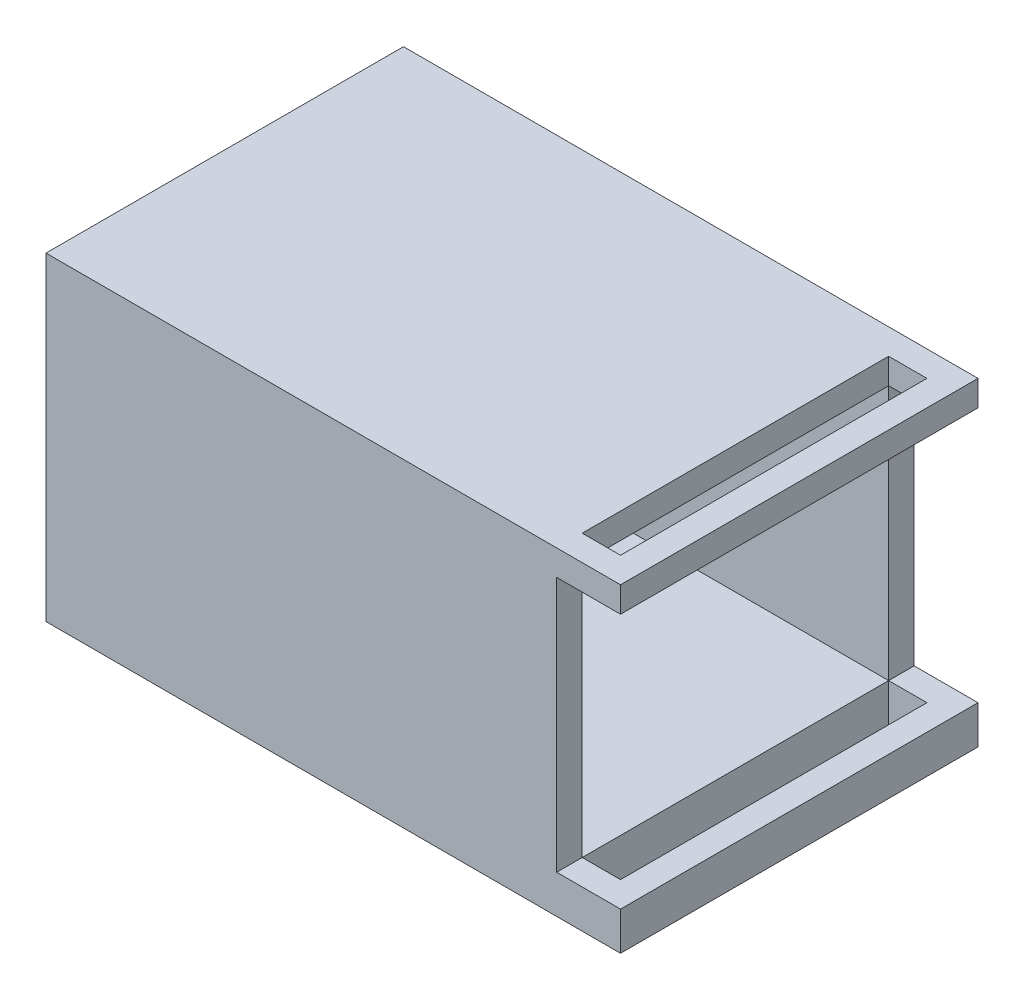
SolidWorks part; units mm, degrees
ref_plane "Front Plane" through (0, 0, 0) normal (0, 0, 1) x (1, 0, 0)
ref_plane "Top Plane" through (0, 0, 0) normal (0, 1, 0) x (1, 0, 0)
ref_plane "Right Plane" through (0, 0, 0) normal (1, 0, 0) x (0, 0, -1)
sketch "Sketch1" plane through (0, 0, 0) normal (0, 1, 0) x (1, 0, 0)
  line L1 (0, 0) -> (45, 0)
  line L2 (0, 0) -> (0, 28)
  line L3 (0, 28) -> (45, 28)
  line L4 (45, 0) -> (45, 28)
  dimension "D1" = 28
  dimension "D2" = 45
extrude "Boss-Extrude1" add sketch "Sketch1" along normal blind 3 contours L2 L1 L4 L3
sketch "Sketch2" plane through (0, 3, 0) normal (0, 1, 0) x (1, 0, 0)
  line L0 (40, 26) -> (40, 28)
  line L1 (0, 28) -> (40, 28)
  line L2 (0, 28) -> (0, 0)
  line L3 (0, 0) -> (40, 0)
  line L5 (2, 26) -> (40, 26)
  line L6 (2, 26) -> (2, 2)
  line L7 (2, 2) -> (40, 2)
  line L9 (40, 2) -> (40, 0)
  line L10 (45, 0) -> (45, 28) construction
  line L11 (0, 0) -> (45, 0) construction
  dimension "D1" = 2
  dimension "D2" = 2
  dimension "D3" = 2
  dimension "D4" = 5
  dimension "D5" = 5
extrude "Boss-Extrude2" add sketch "Sketch2" along normal blind 22 contours L5 L0 L1 L2 L3 L9 L7 L6
sketch "Sketch4" plane through (0, 25, 0) normal (0, 1, 0) x (1, 0, 0)
  line L0 (0, 28) -> (40, 28) construction
  line L1 (0, 28) -> (45, 28)
  line L2 (0, 28) -> (0, 0)
  line L3 (0, 0) -> (45, 0)
  line L4 (45, 28) -> (45, 0)
  line L5 (2, 2) -> (40, 2) construction
  line L6 (40, 26) -> (43, 26)
  line L7 (40, 26) -> (40, 2)
  line L8 (40, 2) -> (43, 2)
  line L9 (43, 26) -> (43, 2)
  dimension "D1" = 2
extrude "Boss-Extrude4" add sketch "Sketch4" against normal blind 2
sketch "Sketch5" plane through (0, 0, 0) normal (-1, 0, 0) x (0, 0, 1)
  line L0 (-18.72, 5.25) -> (-18.72, 5.96)
  line L1 (-17.47, 4) -> (-10.53, 4)
  line L2 (-17.47, 7.21) -> (-10.53, 7.21)
  line L3 (-9.28, 5.96) -> (-9.28, 5.25)
  line L4 (0, 0) -> (-28, 0) construction
  line L5 (-28, 25) -> (-28, 0) construction
  line L6 (0, 25) -> (0, 0) construction
  line L7 (-18.5, 12) -> (-9.5, 12)
  line L8 (-18.5, 12) -> (-18.5, 8.5)
  line L9 (-18.5, 8.5) -> (-9.5, 8.5)
  line L10 (-9.5, 12) -> (-9.5, 8.5)
  arc A0 (-18.72, 5.25) -> (-17.47, 4) centre (-17.47, 5.25) ccw
  arc A1 (-17.47, 7.21) -> (-18.72, 5.96) centre (-17.47, 5.96) ccw
  arc A2 (-9.28, 5.96) -> (-10.53, 7.21) centre (-10.53, 5.96) ccw
  arc A3 (-10.53, 4) -> (-9.28, 5.25) centre (-10.53, 5.25) ccw
  dimension "D7" = 1.25
  dimension "D1" = 1.25
  dimension "D2" = 0.71
  dimension "D3" = 6.94
  dimension "D4" = 1.25
  dimension "D5" = 1.25
  dimension "D6" = 6.94
  dimension "D8" = 3.21
  dimension "D9" = 0.71
  dimension "D10" = 4
  dimension "D11" = 9.28
  dimension "D12" = 3.5
  dimension "D13" = 9
  dimension "D14" = 1.29
  dimension "D15" = 0.22
  dimension "D16" = 0.22
  dimension "D17" = 9.28
extrude "Cut-Extrude1" cut sketch "Sketch5" against normal blind 2
sketch "Sketch6" plane through (0, 3, 0) normal (0, 1, 0) x (1, 0, 0)
  line L0 (45, 0) -> (45, 28) construction
  line L1 (43, 2) -> (40, 2)
  line L2 (43, 2) -> (43, 26)
  line L3 (43, 26) -> (40, 26)
  line L4 (40, 2) -> (40, 26)
  line L5 (40, 0) -> (45, 0) construction
  line L6 (40, 28) -> (45, 28) construction
  line L7 (40, 26) -> (40, 28) construction
  dimension "D1" = 2
  dimension "D2" = 2
  dimension "D3" = 2
extrude "Cut-Extrude2" cut sketch "Sketch6" against normal blind 3
